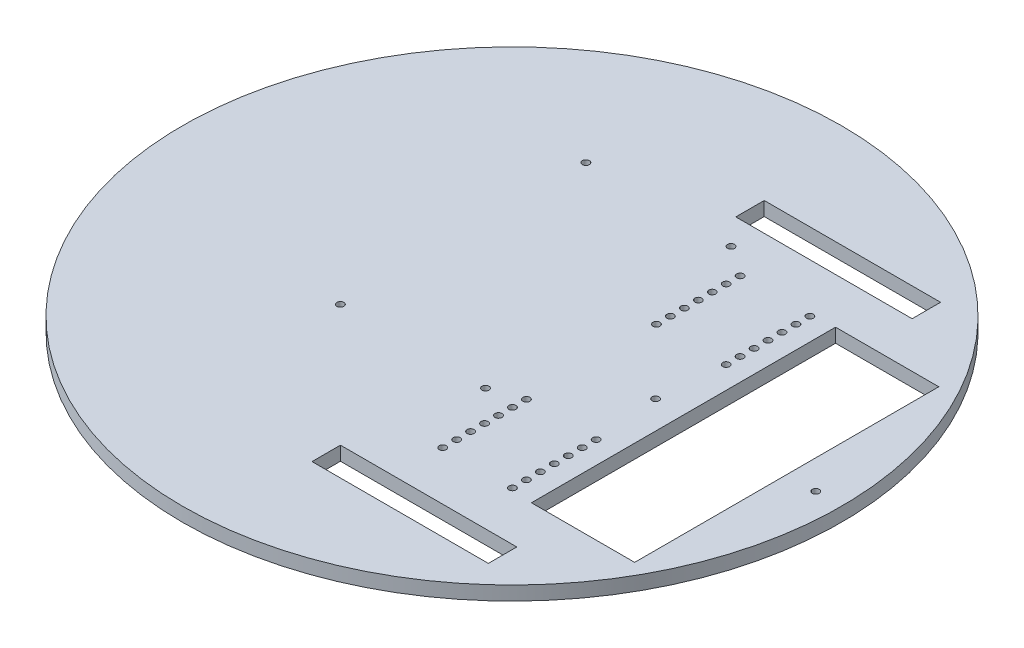
SolidWorks part; units mm, degrees
ref_plane "Front Plane" through (0, 0, 0) normal (0, 0, 1) x (1, 0, 0)
ref_plane "Top Plane" through (0, 0, 0) normal (0, 1, 0) x (1, 0, 0)
ref_plane "Right Plane" through (0, 0, 0) normal (1, 0, 0) x (0, 0, -1)
sketch "Sketch1" plane through (0, 0, 0) normal (0, 1, 0) x (1, 0, 0)
  circle A0 centre (0, 0) radius 150
  dimension "D1" = 300
extrude "Boss-Extrude1" add sketch "Sketch1" against normal blind 6.35
sketch "Sketch2" plane through (0, 0, 0) normal (0, 1, 0) x (1, 0, 0)
  line L0 (36.144, -67.691) -> (36.144, -61.341) construction
  line L1 (52.019, 0) -> (52.019, -89.9668) construction
  line L2 (11.887, -89.9668) -> (92.151, -89.9668)
  line L3 (11.887, -89.9668) -> (11.887, -102.9208)
  line L4 (11.887, -102.9208) -> (92.151, -102.9208)
  line L5 (92.151, -89.9668) -> (92.151, -102.9208)
  line L6 (11.887, 89.9668) -> (92.151, 89.9668)
  line L7 (11.887, 89.9668) -> (11.887, 102.9208)
  line L8 (11.887, 102.9208) -> (92.151, 102.9208)
  line L9 (92.151, 89.9668) -> (92.151, 102.9208)
  line L10 (52.019, 0) -> (52.019, 89.9668) construction
  line L11 (36.144, -61.341) -> (36.144, -54.991) construction
  line L12 (36.144, -54.991) -> (36.144, -48.641) construction
  line L13 (36.144, -48.641) -> (36.144, -42.291) construction
  line L14 (36.144, -42.291) -> (36.144, -35.941) construction
  line L15 (36.144, -35.941) -> (36.144, -29.591) construction
  line L16 (67.894, -67.691) -> (67.894, -61.341) construction
  line L17 (67.894, -61.341) -> (67.894, -54.991) construction
  line L18 (67.894, -54.991) -> (67.894, -48.641) construction
  line L19 (67.894, -48.641) -> (67.894, -42.291) construction
  line L20 (67.894, -42.291) -> (67.894, -35.941) construction
  line L21 (67.894, -35.941) -> (67.894, -29.591) construction
  line L22 (36.144, -67.691) -> (67.894, -67.691) construction
  line L23 (36.144, -29.591) -> (67.894, -29.591) construction
  line L24 (36.144, 29.591) -> (36.144, 35.941) construction
  line L25 (36.144, 35.941) -> (36.144, 42.291) construction
  line L26 (36.144, 42.291) -> (36.144, 48.641) construction
  line L27 (36.144, 48.641) -> (36.144, 54.991) construction
  line L28 (36.144, 54.991) -> (36.144, 61.341) construction
  line L29 (36.144, 61.341) -> (36.144, 67.691) construction
  line L30 (67.894, 29.591) -> (67.894, 35.941) construction
  line L31 (67.894, 35.941) -> (67.894, 42.291) construction
  line L32 (67.894, 42.291) -> (67.894, 48.641) construction
  line L33 (67.894, 48.641) -> (67.894, 54.991) construction
  line L34 (67.894, 54.991) -> (67.894, 61.341) construction
  line L35 (67.894, 61.341) -> (67.894, 67.691) construction
  line L36 (36.144, 67.691) -> (67.894, 67.691) construction
  line L37 (36.144, 29.591) -> (67.894, 29.591) construction
  line L38 (36.144, 48.641) -> (52.019, 48.641) construction
  line L39 (52.019, 48.641) -> (67.894, 48.641) construction
  line L40 (0, -150) -> (0, 150) construction
  line L41 (0, 0) -> (52.019, 0) construction
  circle A1 centre (36.144, -67.691) radius 1.5875
  circle A2 centre (36.144, -61.341) radius 1.5875
  circle A3 centre (36.144, -54.991) radius 1.5875
  circle A4 centre (36.144, -48.641) radius 1.5875
  circle A5 centre (36.144, -42.291) radius 1.5875
  circle A6 centre (36.144, -35.941) radius 1.5875
  circle A7 centre (36.144, -29.591) radius 1.5875
  circle A8 centre (67.894, -67.691) radius 1.5875
  circle A9 centre (67.894, -61.341) radius 1.5875
  circle A10 centre (67.894, -54.991) radius 1.5875
  circle A11 centre (67.894, -48.641) radius 1.5875
  circle A12 centre (67.894, -42.291) radius 1.5875
  circle A13 centre (67.894, -35.941) radius 1.5875
  circle A14 centre (67.894, -29.591) radius 1.5875
  circle A15 centre (36.144, 67.691) radius 1.5875
  circle A16 centre (36.144, 61.341) radius 1.5875
  circle A17 centre (36.144, 54.991) radius 1.5875
  circle A18 centre (36.144, 48.641) radius 1.5875
  circle A19 centre (36.144, 42.291) radius 1.5875
  circle A20 centre (36.144, 35.941) radius 1.5875
  circle A21 centre (36.144, 29.591) radius 1.5875
  circle A22 centre (67.894, 67.691) radius 1.5875
  circle A23 centre (67.894, 61.341) radius 1.5875
  circle A24 centre (67.894, 54.991) radius 1.5875
  circle A25 centre (67.894, 48.641) radius 1.5875
  circle A26 centre (67.894, 42.291) radius 1.5875
  circle A27 centre (67.894, 35.941) radius 1.5875
  circle A28 centre (67.894, 29.591) radius 1.5875
  circle A29 centre (0, 0) radius 150 construction
  dimension "D6" = 3.175
  dimension "D7" = 6.35
  dimension "D8" = 15.875
  dimension "D10" = 3.175
  dimension "D1" = 12.954
  dimension "D2" = 80.264
  dimension "D3" = 179.9336
  dimension "D4" = 22.2758
  dimension "D5" = 15.875
  dimension "D9" = 15.875
  dimension "D11" = 6.35
  dimension "D12" = 22.2758
  dimension "D13" = 59.182
extrude "Cut-Extrude1" cut sketch "Sketch2" against normal through all
sketch "Sketch3" plane through (0, 0, 0) normal (0, 1, 0) x (1, 0, 0)
  line L0 (-43.612, -34.4932) -> (-43.612, 77.2668) construction
  line L1 (-43.612, 77.2668) -> (22.428, 77.2668) construction
  line L2 (22.428, 77.2668) -> (22.428, -34.4932) construction
  line L3 (22.428, -34.4932) -> (-43.612, -34.4932) construction
  line L4 (11.887, 89.9668) -> (92.151, 89.9668) construction
  circle A0 centre (-43.612, 77.2668) radius 1.5875
  circle A1 centre (22.428, 77.2668) radius 1.5875
  circle A2 centre (22.428, -34.4932) radius 1.5875
  circle A3 centre (-43.612, -34.4932) radius 1.5875
  circle A4 centre (36.144, 67.691) radius 1.5875 construction
  dimension "D1" = 3.175
  dimension "D2" = 111.76
  dimension "D3" = 66.04
  dimension "D4" = 12.7
  dimension "D5" = 13.716
extrude "Cut-Extrude2" cut sketch "Sketch3" against normal through all
sketch "Sketch4" plane through (0, 0, 0) normal (0, 1, 0) x (1, 0, 0)
  line L0 (78.054, -69.215) -> (78.054, -89.9668) construction
  line L1 (78.054, 69.215) -> (125.044, 69.215)
  line L2 (78.054, 69.215) -> (78.054, -69.215)
  line L3 (78.054, -69.215) -> (125.044, -69.215)
  line L4 (125.044, 69.215) -> (125.044, -69.215)
  line L5 (92.151, -89.9668) -> (11.887, -89.9668) construction
  line L6 (78.054, 69.215) -> (78.054, 89.9668) construction
  line L7 (11.887, 89.9668) -> (92.151, 89.9668) construction
  line L8 (65.354, 0) -> (78.054, 0) construction
  line L9 (78.054, 0) -> (125.044, 0) construction
  line L10 (125.044, 0) -> (138.252, 0) construction
  circle A1 centre (67.894, 29.591) radius 1.5875 construction
  circle A4 centre (65.354, 0) radius 1.5875
  circle A5 centre (138.252, 0) radius 1.5875
  dimension "D3" = 3.175
  dimension "D6" = 10.16
  dimension "D1" = 138.43
  dimension "D2" = 46.99
  dimension "D4" = 12.7
  dimension "D5" = 13.208
ref_plane "Plane1" through (92.151, 0, -89.9668) normal (1, 0, 0) x (0, 0, -1)
extrude "Cut-Extrude3" cut sketch "Sketch4" against normal through all
